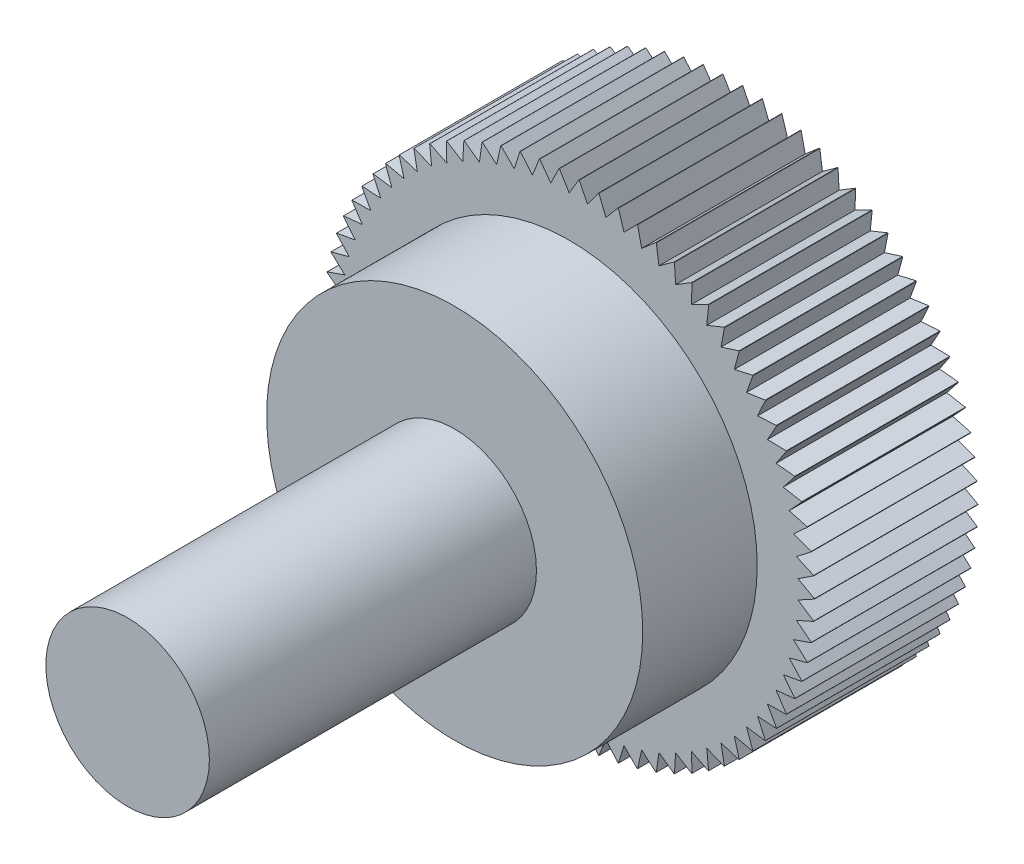
SolidWorks part; units mm, degrees
ref_plane "Front" through (0, 0, 0) normal (0, 0, 1) x (1, 0, 0)
ref_plane "Top" through (0, 0, 0) normal (0, 1, 0) x (1, 0, 0)
ref_plane "Right" through (0, 0, 0) normal (1, 0, 0) x (0, 0, -1)
sketch "Sketch1" plane through (0, 0, 0) normal (0, 0, 1) x (1, 0, 0)
  circle A0 centre (0, 0) radius 7.5
  dimension "D1" = 15
extrude "Extrude1" add sketch "Sketch1" along normal blind 5
sketch "Sketch2" plane through (0, 0, 5) normal (0, 0, 1) x (1, 0, 0)
  circle A0 centre (0, 0) radius 5.75
  dimension "D1" = 11.5
extrude "Extrude2" add sketch "Sketch2" along normal blind 3.5
sketch "Sketch3" plane through (0, 0, 8.5) normal (0, 0, 1) x (1, 0, 0)
  circle A0 centre (0, 0) radius 2.5
  dimension "D1" = 5
extrude "Extrude3" add sketch "Sketch3" along normal blind 10
sketch "Sketch4" plane through (0, 0, 0) normal (0, 0, -1) x (-1, 0, 0)
  line L0 (0, 0) -> (0, 7.5) construction
  line L1 (-0.3, 7.5) -> (0, 7)
  line L2 (0.3, 7.5) -> (0, 7)
  line L3 (-0.3, 7.5) -> (0.3, 7.5)
  line L4 (0.3045, 7.4998) -> (0.5633, 6.9773)
  line L5 (0.9025, 7.4515) -> (0.5633, 6.9773)
  line L6 (0.3045, 7.4998) -> (0.9025, 7.4515)
  line L7 (0.907, 7.451) -> (1.1229, 6.9094)
  line L8 (1.4992, 7.3548) -> (1.1229, 6.9094)
  line L9 (0.907, 7.451) -> (1.4992, 7.3548)
  line L10 (1.5036, 7.3539) -> (1.6752, 6.7966)
  line L11 (2.0862, 7.2103) -> (1.6752, 6.7966)
  line L12 (1.5036, 7.3539) -> (2.0862, 7.2103)
  line L13 (2.0904, 7.209) -> (2.2167, 6.6398)
  line L14 (2.6596, 7.019) -> (2.2167, 6.6398)
  line L15 (2.0904, 7.209) -> (2.6596, 7.019)
  line L16 (2.6638, 7.0174) -> (2.7438, 6.4399)
  line L17 (3.2157, 6.7823) -> (2.7438, 6.4399)
  line L18 (2.6638, 7.0174) -> (3.2157, 6.7823)
  line L19 (3.2198, 6.7803) -> (3.2531, 6.1982)
  line L20 (3.7511, 6.5015) -> (3.2531, 6.1982)
  line L21 (3.2198, 6.7803) -> (3.7511, 6.5015)
  line L22 (3.7549, 6.4993) -> (3.7413, 5.9163)
  line L23 (4.2621, 6.1786) -> (3.7413, 5.9163)
  line L24 (3.7549, 6.4993) -> (4.2621, 6.1786)
  line L25 (4.2657, 6.176) -> (4.2052, 5.5961)
  line L26 (4.7454, 5.8156) -> (4.2052, 5.5961)
  line L27 (4.2657, 6.176) -> (4.7454, 5.8156)
  line L28 (4.7489, 5.8128) -> (4.6419, 5.2396)
  line L29 (5.198, 5.4149) -> (4.6419, 5.2396)
  line L30 (4.7489, 5.8128) -> (5.198, 5.4149)
  line L31 (5.2012, 5.4118) -> (5.0484, 4.8491)
  line L32 (5.6168, 4.9791) -> (5.0484, 4.8491)
  line L33 (5.2012, 5.4118) -> (5.6168, 4.9791)
  line L34 (5.6198, 4.9757) -> (5.4222, 4.4271)
  line L35 (5.9993, 4.511) -> (5.4222, 4.4271)
  line L36 (5.6198, 4.9757) -> (5.9993, 4.511)
  line L37 (6.002, 4.5074) -> (5.7609, 3.9765)
  line L38 (6.3428, 4.0136) -> (5.7609, 3.9765)
  line L39 (6.002, 4.5074) -> (6.3428, 4.0136)
  line L40 (6.3452, 4.0098) -> (6.0622, 3.5)
  line L41 (6.6452, 3.4902) -> (6.0622, 3.5)
  line L42 (6.3452, 4.0098) -> (6.6452, 3.4902)
  line L43 (6.6473, 3.4862) -> (6.3242, 3.0008)
  line L44 (6.9045, 2.9442) -> (6.3242, 3.0008)
  line L45 (6.6473, 3.4862) -> (6.9045, 2.9442)
  line L46 (6.9062, 2.94) -> (6.5451, 2.4822)
  line L47 (7.119, 2.379) -> (6.5451, 2.4822)
  line L48 (6.9062, 2.94) -> (7.119, 2.379)
  line L49 (7.1204, 2.3748) -> (6.7236, 1.9475)
  line L50 (7.2874, 1.7985) -> (6.7236, 1.9475)
  line L51 (7.1204, 2.3748) -> (7.2874, 1.7985)
  line L52 (7.2884, 1.7941) -> (6.8585, 1.4002)
  line L53 (7.4084, 1.2063) -> (6.8585, 1.4002)
  line L54 (7.2884, 1.7941) -> (7.4084, 1.2063)
  line L55 (7.4092, 1.2018) -> (6.949, 0.8438)
  line L56 (7.4815, 0.6062) -> (6.949, 0.8438)
  line L57 (7.4092, 1.2018) -> (7.4815, 0.6062)
  line L58 (7.4818, 0.6018) -> (6.9943, 0.2819)
  line L59 (7.506, 0.0022) -> (6.9943, 0.2819)
  line L60 (7.4818, 0.6018) -> (7.506, 0.0022)
  line L61 (7.506, -0.0022) -> (6.9943, -0.2819)
  line L62 (7.4818, -0.6018) -> (6.9943, -0.2819)
  line L63 (7.506, -0.0022) -> (7.4818, -0.6018)
  line L64 (7.4815, -0.6062) -> (6.949, -0.8438)
  line L65 (7.4092, -1.2018) -> (6.949, -0.8438)
  line L66 (7.4815, -0.6062) -> (7.4092, -1.2018)
  line L67 (7.4084, -1.2063) -> (6.8585, -1.4002)
  line L68 (7.2884, -1.7941) -> (6.8585, -1.4002)
  line L69 (7.4084, -1.2063) -> (7.2884, -1.7941)
  line L70 (7.2874, -1.7985) -> (6.7236, -1.9475)
  line L71 (7.1204, -2.3748) -> (6.7236, -1.9475)
  line L72 (7.2874, -1.7985) -> (7.1204, -2.3748)
  line L73 (7.119, -2.379) -> (6.5451, -2.4822)
  line L74 (6.9062, -2.94) -> (6.5451, -2.4822)
  line L75 (7.119, -2.379) -> (6.9062, -2.94)
  line L76 (6.9045, -2.9442) -> (6.3242, -3.0008)
  line L77 (6.6473, -3.4862) -> (6.3242, -3.0008)
  line L78 (6.9045, -2.9442) -> (6.6473, -3.4862)
  line L79 (6.6452, -3.4902) -> (6.0622, -3.5)
  line L80 (6.3452, -4.0098) -> (6.0622, -3.5)
  line L81 (6.6452, -3.4902) -> (6.3452, -4.0098)
  line L82 (6.3428, -4.0136) -> (5.7609, -3.9765)
  line L83 (6.002, -4.5074) -> (5.7609, -3.9765)
  line L84 (6.3428, -4.0136) -> (6.002, -4.5074)
  line L85 (5.9993, -4.511) -> (5.4222, -4.4271)
  line L86 (5.6198, -4.9757) -> (5.4222, -4.4271)
  line L87 (5.9993, -4.511) -> (5.6198, -4.9757)
  line L88 (5.6168, -4.9791) -> (5.0484, -4.8491)
  line L89 (5.2012, -5.4118) -> (5.0484, -4.8491)
  line L90 (5.6168, -4.9791) -> (5.2012, -5.4118)
  line L91 (5.198, -5.4149) -> (4.6419, -5.2396)
  line L92 (4.7489, -5.8128) -> (4.6419, -5.2396)
  line L93 (5.198, -5.4149) -> (4.7489, -5.8128)
  line L94 (4.7454, -5.8156) -> (4.2052, -5.5961)
  line L95 (4.2657, -6.176) -> (4.2052, -5.5961)
  line L96 (4.7454, -5.8156) -> (4.2657, -6.176)
  line L97 (4.2621, -6.1786) -> (3.7413, -5.9163)
  line L98 (3.7549, -6.4993) -> (3.7413, -5.9163)
  line L99 (4.2621, -6.1786) -> (3.7549, -6.4993)
  line L100 (3.7511, -6.5015) -> (3.2531, -6.1982)
  line L101 (3.2198, -6.7803) -> (3.2531, -6.1982)
  line L102 (3.7511, -6.5015) -> (3.2198, -6.7803)
  line L103 (3.2157, -6.7823) -> (2.7438, -6.4399)
  line L104 (2.6638, -7.0174) -> (2.7438, -6.4399)
  line L105 (3.2157, -6.7823) -> (2.6638, -7.0174)
  line L106 (2.6596, -7.019) -> (2.2167, -6.6398)
  line L107 (2.0904, -7.209) -> (2.2167, -6.6398)
  line L108 (2.6596, -7.019) -> (2.0904, -7.209)
  line L109 (2.0862, -7.2103) -> (1.6752, -6.7966)
  line L110 (1.5036, -7.3539) -> (1.6752, -6.7966)
  line L111 (2.0862, -7.2103) -> (1.5036, -7.3539)
  line L112 (1.4992, -7.3548) -> (1.1229, -6.9094)
  line L113 (0.907, -7.451) -> (1.1229, -6.9094)
  line L114 (1.4992, -7.3548) -> (0.907, -7.451)
  line L115 (0.9025, -7.4515) -> (0.5633, -6.9773)
  line L116 (0.3045, -7.4998) -> (0.5633, -6.9773)
  line L117 (0.9025, -7.4515) -> (0.3045, -7.4998)
  line L118 (0.3, -7.5) -> (0, -7)
  line L119 (-0.3, -7.5) -> (0, -7)
  line L120 (0.3, -7.5) -> (-0.3, -7.5)
  line L121 (-0.3045, -7.4998) -> (-0.5633, -6.9773)
  line L122 (-0.9025, -7.4515) -> (-0.5633, -6.9773)
  line L123 (-0.3045, -7.4998) -> (-0.9025, -7.4515)
  line L124 (-0.907, -7.451) -> (-1.1229, -6.9094)
  line L125 (-1.4992, -7.3548) -> (-1.1229, -6.9094)
  line L126 (-0.907, -7.451) -> (-1.4992, -7.3548)
  line L127 (-1.5036, -7.3539) -> (-1.6752, -6.7966)
  line L128 (-2.0862, -7.2103) -> (-1.6752, -6.7966)
  line L129 (-1.5036, -7.3539) -> (-2.0862, -7.2103)
  line L130 (-2.0904, -7.209) -> (-2.2167, -6.6398)
  line L131 (-2.6596, -7.019) -> (-2.2167, -6.6398)
  line L132 (-2.0904, -7.209) -> (-2.6596, -7.019)
  line L133 (-2.6638, -7.0174) -> (-2.7438, -6.4399)
  line L134 (-3.2157, -6.7823) -> (-2.7438, -6.4399)
  line L135 (-2.6638, -7.0174) -> (-3.2157, -6.7823)
  line L136 (-3.2198, -6.7803) -> (-3.2531, -6.1982)
  line L137 (-3.7511, -6.5015) -> (-3.2531, -6.1982)
  line L138 (-3.2198, -6.7803) -> (-3.7511, -6.5015)
  line L139 (-3.7549, -6.4993) -> (-3.7413, -5.9163)
  line L140 (-4.2621, -6.1786) -> (-3.7413, -5.9163)
  line L141 (-3.7549, -6.4993) -> (-4.2621, -6.1786)
  line L142 (-4.2657, -6.176) -> (-4.2052, -5.5961)
  line L143 (-4.7454, -5.8156) -> (-4.2052, -5.5961)
  line L144 (-4.2657, -6.176) -> (-4.7454, -5.8156)
  line L145 (-4.7489, -5.8128) -> (-4.6419, -5.2396)
  line L146 (-5.198, -5.4149) -> (-4.6419, -5.2396)
  line L147 (-4.7489, -5.8128) -> (-5.198, -5.4149)
  line L148 (-5.2012, -5.4118) -> (-5.0484, -4.8491)
  line L149 (-5.6168, -4.9791) -> (-5.0484, -4.8491)
  line L150 (-5.2012, -5.4118) -> (-5.6168, -4.9791)
  line L151 (-5.6198, -4.9757) -> (-5.4222, -4.4271)
  line L152 (-5.9993, -4.511) -> (-5.4222, -4.4271)
  line L153 (-5.6198, -4.9757) -> (-5.9993, -4.511)
  line L154 (-6.002, -4.5074) -> (-5.7609, -3.9765)
  line L155 (-6.3428, -4.0136) -> (-5.7609, -3.9765)
  line L156 (-6.002, -4.5074) -> (-6.3428, -4.0136)
  line L157 (-6.3452, -4.0098) -> (-6.0622, -3.5)
  line L158 (-6.6452, -3.4902) -> (-6.0622, -3.5)
  line L159 (-6.3452, -4.0098) -> (-6.6452, -3.4902)
  line L160 (-6.6473, -3.4862) -> (-6.3242, -3.0008)
  line L161 (-6.9045, -2.9442) -> (-6.3242, -3.0008)
  line L162 (-6.6473, -3.4862) -> (-6.9045, -2.9442)
  line L163 (-6.9062, -2.94) -> (-6.5451, -2.4822)
  line L164 (-7.119, -2.379) -> (-6.5451, -2.4822)
  line L165 (-6.9062, -2.94) -> (-7.119, -2.379)
  line L166 (-7.1204, -2.3748) -> (-6.7236, -1.9475)
  line L167 (-7.2874, -1.7985) -> (-6.7236, -1.9475)
  line L168 (-7.1204, -2.3748) -> (-7.2874, -1.7985)
  line L169 (-7.2884, -1.7941) -> (-6.8585, -1.4002)
  line L170 (-7.4084, -1.2063) -> (-6.8585, -1.4002)
  line L171 (-7.2884, -1.7941) -> (-7.4084, -1.2063)
  line L172 (-7.4092, -1.2018) -> (-6.949, -0.8438)
  line L173 (-7.4815, -0.6062) -> (-6.949, -0.8438)
  line L174 (-7.4092, -1.2018) -> (-7.4815, -0.6062)
  line L175 (-7.4818, -0.6018) -> (-6.9943, -0.2819)
  line L176 (-7.506, -0.0022) -> (-6.9943, -0.2819)
  line L177 (-7.4818, -0.6018) -> (-7.506, -0.0022)
  line L178 (-7.506, 0.0022) -> (-6.9943, 0.2819)
  line L179 (-7.4818, 0.6018) -> (-6.9943, 0.2819)
  line L180 (-7.506, 0.0022) -> (-7.4818, 0.6018)
  line L181 (-7.4815, 0.6062) -> (-6.949, 0.8438)
  line L182 (-7.4092, 1.2018) -> (-6.949, 0.8438)
  line L183 (-7.4815, 0.6062) -> (-7.4092, 1.2018)
  line L184 (-7.4084, 1.2063) -> (-6.8585, 1.4002)
  line L185 (-7.2884, 1.7941) -> (-6.8585, 1.4002)
  line L186 (-7.4084, 1.2063) -> (-7.2884, 1.7941)
  line L187 (-7.2874, 1.7985) -> (-6.7236, 1.9475)
  line L188 (-7.1204, 2.3748) -> (-6.7236, 1.9475)
  line L189 (-7.2874, 1.7985) -> (-7.1204, 2.3748)
  line L190 (-7.119, 2.379) -> (-6.5451, 2.4822)
  line L191 (-6.9062, 2.94) -> (-6.5451, 2.4822)
  line L192 (-7.119, 2.379) -> (-6.9062, 2.94)
  line L193 (-6.9045, 2.9442) -> (-6.3242, 3.0008)
  line L194 (-6.6473, 3.4862) -> (-6.3242, 3.0008)
  line L195 (-6.9045, 2.9442) -> (-6.6473, 3.4862)
  line L196 (-6.6452, 3.4902) -> (-6.0622, 3.5)
  line L197 (-6.3452, 4.0098) -> (-6.0622, 3.5)
  line L198 (-6.6452, 3.4902) -> (-6.3452, 4.0098)
  line L199 (-6.3428, 4.0136) -> (-5.7609, 3.9765)
  line L200 (-6.002, 4.5074) -> (-5.7609, 3.9765)
  line L201 (-6.3428, 4.0136) -> (-6.002, 4.5074)
  line L202 (-5.9993, 4.511) -> (-5.4222, 4.4271)
  line L203 (-5.6198, 4.9757) -> (-5.4222, 4.4271)
  line L204 (-5.9993, 4.511) -> (-5.6198, 4.9757)
  line L205 (-5.6168, 4.9791) -> (-5.0484, 4.8491)
  line L206 (-5.2012, 5.4118) -> (-5.0484, 4.8491)
  line L207 (-5.6168, 4.9791) -> (-5.2012, 5.4118)
  line L208 (-5.198, 5.4149) -> (-4.6419, 5.2396)
  line L209 (-4.7489, 5.8128) -> (-4.6419, 5.2396)
  line L210 (-5.198, 5.4149) -> (-4.7489, 5.8128)
  line L211 (-4.7454, 5.8156) -> (-4.2052, 5.5961)
  line L212 (-4.2657, 6.176) -> (-4.2052, 5.5961)
  line L213 (-4.7454, 5.8156) -> (-4.2657, 6.176)
  line L214 (-4.2621, 6.1786) -> (-3.7413, 5.9163)
  line L215 (-3.7549, 6.4993) -> (-3.7413, 5.9163)
  line L216 (-4.2621, 6.1786) -> (-3.7549, 6.4993)
  line L217 (-3.7511, 6.5015) -> (-3.2531, 6.1982)
  line L218 (-3.2198, 6.7803) -> (-3.2531, 6.1982)
  line L219 (-3.7511, 6.5015) -> (-3.2198, 6.7803)
  line L220 (-3.2157, 6.7823) -> (-2.7438, 6.4399)
  line L221 (-2.6638, 7.0174) -> (-2.7438, 6.4399)
  line L222 (-3.2157, 6.7823) -> (-2.6638, 7.0174)
  line L223 (-2.6596, 7.019) -> (-2.2167, 6.6398)
  line L224 (-2.0904, 7.209) -> (-2.2167, 6.6398)
  line L225 (-2.6596, 7.019) -> (-2.0904, 7.209)
  line L226 (-2.0862, 7.2103) -> (-1.6752, 6.7966)
  line L227 (-1.5036, 7.3539) -> (-1.6752, 6.7966)
  line L228 (-2.0862, 7.2103) -> (-1.5036, 7.3539)
  line L229 (-1.4992, 7.3548) -> (-1.1229, 6.9094)
  line L230 (-0.907, 7.451) -> (-1.1229, 6.9094)
  line L231 (-1.4992, 7.3548) -> (-0.907, 7.451)
  line L232 (-0.9025, 7.4515) -> (-0.5633, 6.9773)
  line L233 (-0.3045, 7.4998) -> (-0.5633, 6.9773)
  line L234 (-0.9025, 7.4515) -> (-0.3045, 7.4998)
  circle A0 centre (0, 0) radius 7.5 construction
  dimension "D1" = 0.3
  dimension "D2" = 0.5
extrude "Cut-Extrude1" cut sketch "Sketch4" against normal blind 20
